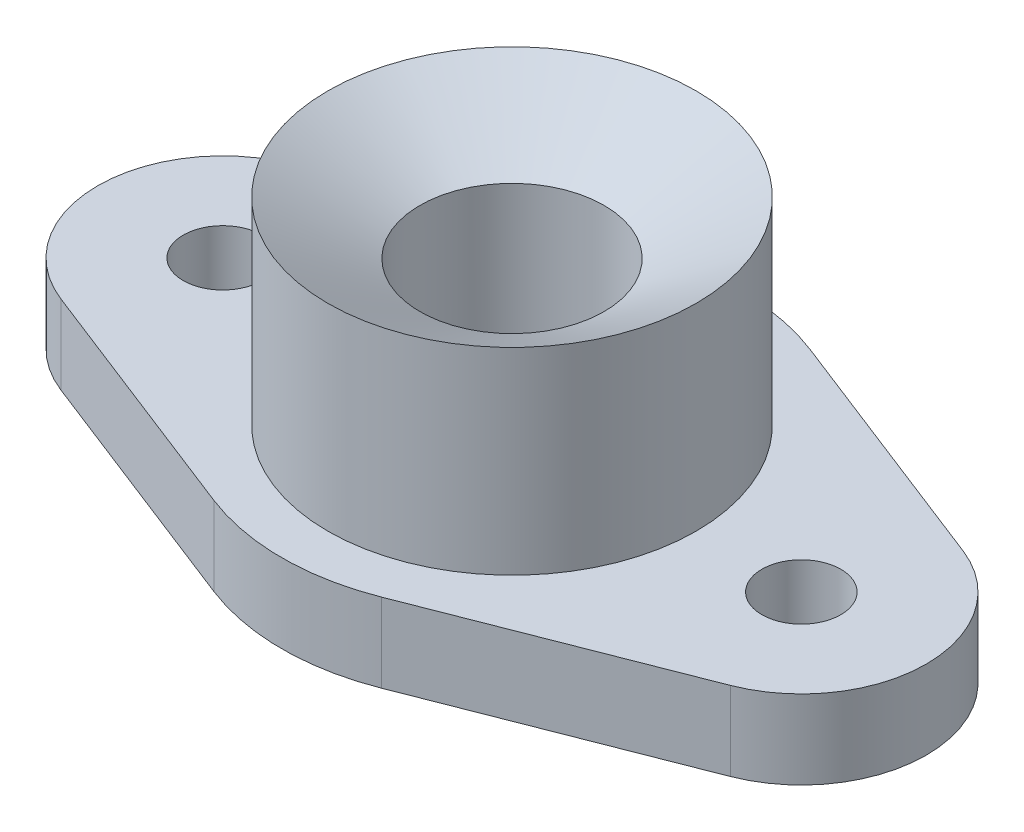
SolidWorks part; units mm, degrees
ref_plane "Front Plane" through (0, 0, 0) normal (0, 0, 1) x (1, 0, 0)
ref_plane "Top Plane" through (0, 0, 0) normal (0, 1, 0) x (1, 0, 0)
ref_plane "Right Plane" through (0, 0, 0) normal (1, 0, 0) x (0, 0, -1)
sketch "Sketch1" plane through (0, 0, 0) normal (0, 1, 0) x (1, 0, 0)
  line L0 (0, 0) -> (0, 25.9667) construction
  line L1 (-50.9091, 17.6993) -> (-12.7273, 32.6039)
  line L2 (0, 0) -> (13.3292, 0) construction
  line L3 (50.9091, 17.6993) -> (12.7273, 32.6039)
  line L4 (50.9091, -17.6993) -> (12.7273, -32.6039)
  line L5 (-50.9091, -17.6993) -> (-12.7273, -32.6039)
  arc A0 (-12.7273, -32.6039) -> (12.7273, -32.6039) centre (0, 0) ccw
  arc A1 (-50.9091, 17.6993) -> (-50.9091, -17.6993) centre (-44, 0) ccw
  arc A2 (50.9091, -17.6993) -> (50.9091, 17.6993) centre (44, 0) ccw
  circle A3 centre (-44, 0) radius 6
  circle A4 centre (44, 0) radius 6
  arc A5 (12.7273, 32.6039) -> (-12.7273, 32.6039) centre (0, 0) ccw
  dimension "D1" = 38
  dimension "D2" = 70
  dimension "D3" = 88
  dimension "D4" = 12
extrude "Boss-Extrude1" add sketch "Sketch1" along normal blind 12
sketch "Sketch2" plane through (0, 0, 0) normal (0, 0, 1) x (1, 0, 0)
  line L0 (0, 0) -> (0, 42) construction
  line L1 (-14, 33.9171) -> (-14, 12)
  line L2 (-14, 12) -> (-28, 12)
  line L3 (-28, 12) -> (-28, 42)
  line L5 (-50.9091, 12) -> (-12.7273, 12) construction
  line L7 (-12.7273, 0) -> (12.7273, 0) construction
  line L8 (-28, 42) -> (-14, 33.9171)
  dimension "D1" = 42
  dimension "D2" = 28
  dimension "D3" = 56
  dimension "D4" = 120
revolve "Revolve1" add sketch "Sketch2" angle 360 about L0
sketch "Sketch3" plane through (0, 12, 0) normal (0, 1, 0) x (1, 0, 0)
  circle A1 centre (0, 0) radius 14
  circle A2 centre (0, 0) radius 14
  dimension "D1" = 0
extrude "Cut-Extrude1" cut sketch "Sketch3" against normal up to next
